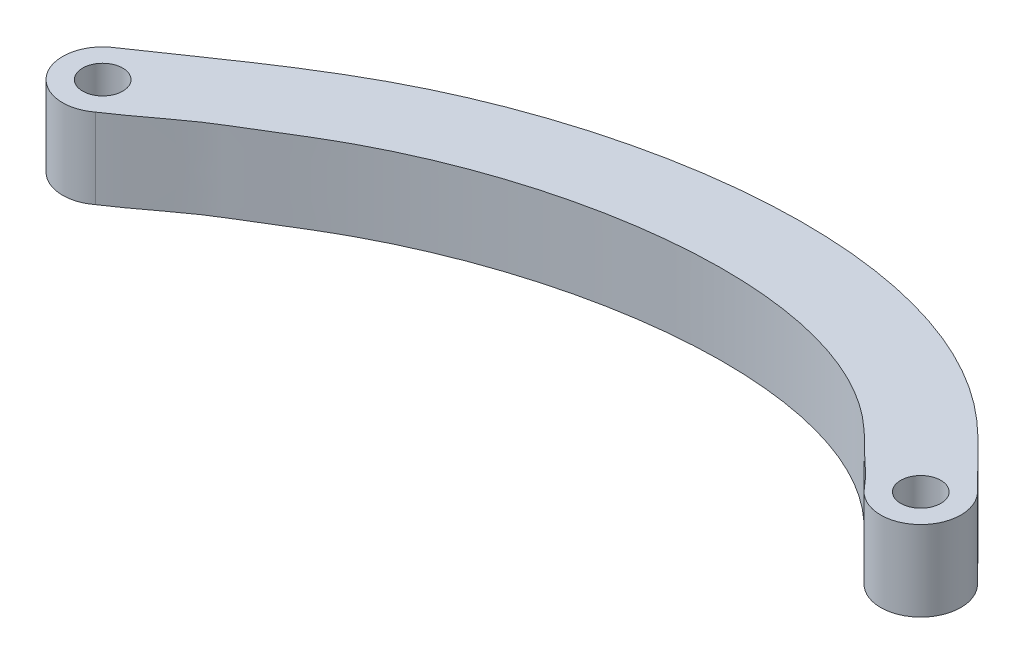
SolidWorks part; units mm, degrees
ref_plane "Front Plane" through (0, 0, 0) normal (0, 0, 1) x (1, 0, 0)
ref_plane "Top Plane" through (0, 0, 0) normal (0, 1, 0) x (1, 0, 0)
ref_plane "Right Plane" through (0, 0, 0) normal (1, 0, 0) x (0, 0, -1)
sketch "Sketch3" plane through (0, 0, 0) normal (0, 1, 0) x (1, 0, 0)
  circle A4 centre (-296.2471, -20.1832) radius 2.5
  circle A5 centre (-200.7107, -13.6961) radius 2.5
  arc A6 (-299.3043, -16.2267) -> (-293.1899, -24.1397) centre (-296.2471, -20.1832) ccw
  arc A7 (-204.4271, -17.0409) -> (-196.9942, -10.3513) centre (-200.7107, -13.6961) ccw
  spline S2 degree 3 poles (-299.3043, -16.2267) (-291.9024, -11.2395) (-266.278, 8.0391) (-218.3235, 13.6233) (-199.9419, -7.4595) (-196.9942, -10.3513) knots 0.847788 0.847788 0.847788 0.847788 28.002369 98.488918 110.926911 110.926911 110.926911 110.926911
  spline S3 degree 3 poles (-293.1899, -24.1397) (-290.1288, -22.1528) (-286.7865, -19.3246) (-280.8624, -15.7721) (-277.6791, -13.7128) (-272.9281, -11.0951) (-271.4828, -10.355) (-268.4849, -8.9435) (-266.9382, -8.2741) (-262.1886, -6.393) (-258.8763, -5.3094) (-251.2713, -3.3408) (-246.9461, -2.5804) (-238.4857, -1.8528) (-234.3519, -1.8867) (-227.64, -2.6791) (-224.9384, -3.2451) (-219.9463, -4.8228) (-217.6572, -5.8324) (-214.7704, -7.547) (-213.984, -8.0694) (-212.5385, -9.142) (-211.8854, -9.6784) (-210.5253, -10.9029) (-209.8291, -11.5818) (-207.7291, -13.7519) (-205.9907, -15.1118) (-204.4271, -17.0409) knots 0.921171 0.921171 0.921171 0.921171 12.454241 12.454241 24.908481 24.908481 30.22679 30.22679 35.5451 35.5451 46.181719 46.181719 59.564678 59.564678 72.947638 72.947638 82.838573 82.838573 92.729507 92.729507 96.661224 96.661224 100.281278 100.281278 103.901331 103.901331 110.926911 110.926911 110.926911 110.926911
  point P3 (0, 0)
extrude "Boss-Extrude1" add sketch "Sketch3" along normal mid plane 10
